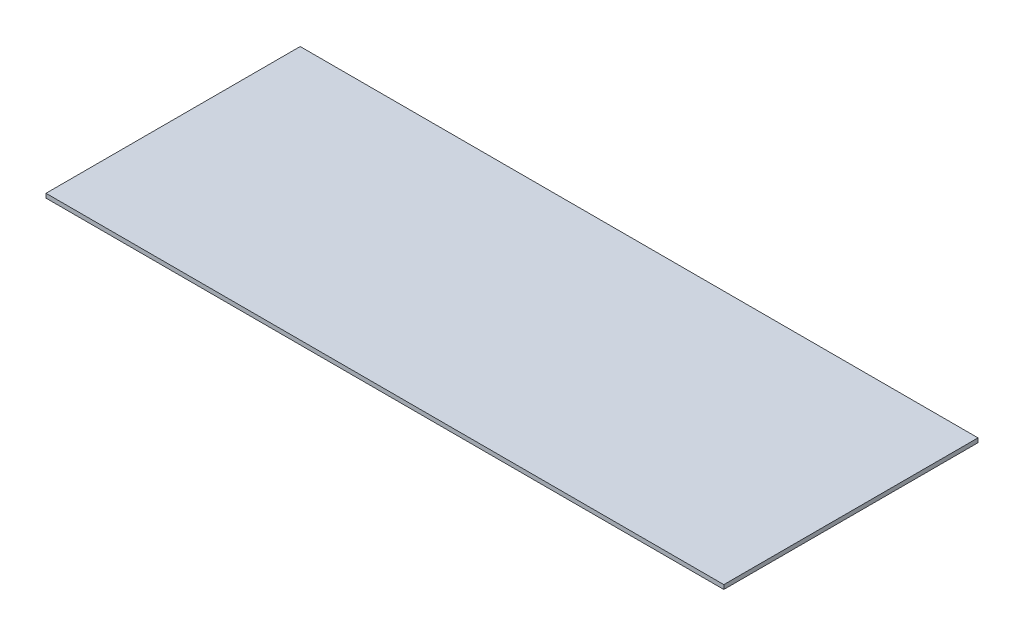
SolidWorks part; units mm, degrees
ref_plane "Front" through (0, 0, 0) normal (0, 0, 1) x (1, 0, 0)
ref_plane "Top" through (0, 0, 0) normal (0, 1, 0) x (1, 0, 0)
ref_plane "Right" through (0, 0, 0) normal (1, 0, 0) x (0, 0, -1)
sketch "草图1" plane through (0, 0, 0) normal (0, 1, 0) x (1, 0, 0)
  line L1 (0, 0) -> (406.4, 0)
  line L2 (0, 0) -> (0, -152.4)
  line L3 (0, -152.4) -> (406.4, -152.4)
  line L4 (406.4, 0) -> (406.4, -152.4)
  dimension "D1" = 152.4
  dimension "D2" = 406.4
extrude "凸台-拉伸1" add sketch "草图1" along normal blind 2.54
